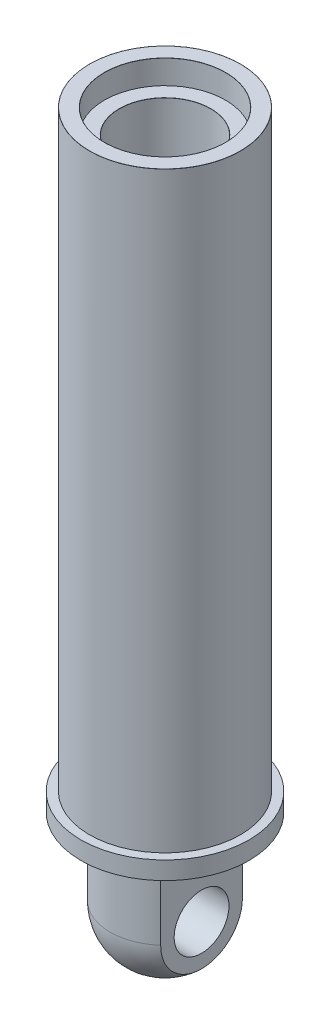
SolidWorks part; units mm, degrees
ref_plane "Front Plane" through (0, 0, 0) normal (0, 0, 1) x (1, 0, 0)
ref_plane "Top Plane" through (0, 0, 0) normal (0, 1, 0) x (1, 0, 0)
ref_plane "Right Plane" through (0, 0, 0) normal (1, 0, 0) x (0, 0, -1)
sketch "Sketch1" plane through (0, 0, 0) normal (0, 0, 1) x (1, 0, 0)
  line L0 (0, 0) -> (0, 300) construction
  line L2 (30.5, 60.44) -> (30.5, 300)
  line L5 (30.5, 300) -> (18.5, 300)
  line L6 (18.5, 300) -> (18.5, 60.44)
  line L7 (18.5, 60.44) -> (0, 60.44)
  line L8 (0, 60.44) -> (0, 0)
  line L9 (22.17, 53.2) -> (34.01, 53.2)
  line L10 (34.01, 53.2) -> (34.01, 60.44)
  line L11 (34.01, 60.44) -> (30.5, 60.44)
  line L16 (22.17, 22.17) -> (22.17, 53.2)
  line L17 (0, 0) -> (44.3568, 0) construction
  arc A2 (0, 0) -> (22.17, 22.17) centre (0, 22.17) ccw
  point P4 (9.25, 60.44)
  dimension "D9" = 22.17
  dimension "D5" = 18.5
  dimension "D3" = 300
  dimension "D1" = 12
  dimension "D4" = 53.2
  dimension "D6" = 7.24
  dimension "D8" = 34.01
revolve "Revolve1" add sketch "Sketch1" angle 360 about L0
cosmetic thread "Cosmetic Thread1" parameters "D1"=146.4852, "D2"=37
sketch "Sketch2" plane through (0, 0, 0) normal (1, 0, 0) x (0, 0, -1)
  circle A0 centre (0, 22.17) radius 11.085
  dimension "D1" = 22.17
  dimension "D2" = 22.17
extrude "Cut-Extrude1" cut sketch "Sketch2" against normal through all both and the other way through all
sketch "Sketch3" plane through (0, 0, 0) normal (0, 0, 1) x (1, 0, 0)
  line L0 (0, 0) -> (0, 49.26) construction
  line L1 (-53.33, 49.26) -> (-53.33, 0)
  line L2 (35.8889, 49.26) -> (53.33, 49.26)
  line L3 (14.78, 28.1481) -> (14.78, 0) construction
  line L4 (14.78, 0) -> (53.33, 0)
  line L5 (53.33, 49.26) -> (53.33, 0)
  line L6 (-35.8889, 49.26) -> (-53.33, 49.26)
  line L7 (-14.78, 0) -> (-53.33, 0)
  line L8 (-14.78, 28.1481) -> (-14.78, 0) construction
  line L9 (14.78, 28.1481) -> (14.78, 49.26)
  line L10 (14.78, 49.26) -> (35.8889, 49.26)
  line L11 (-14.78, 28.1481) -> (-14.78, 49.26)
  line L12 (-14.78, 49.26) -> (-35.8889, 49.26)
  line L13 (-14.78, 28.1481) -> (-14.78, 0)
  line L14 (14.78, 0) -> (14.78, 28.1481)
  arc A1 (-35.8889, 49.26) -> (-14.78, 28.1481) centre (-35.8911, 28.1489) cw construction
  dimension "D1" = 49.26
  dimension "D2" = 38.55
  dimension "D3" = 14.78
extrude "Cut-Extrude2" cut sketch "Sketch3" against normal through all both and the other way through all
fillet "Fillet1" radius 0.1468 3 edges at (22.17, 53.2, 0) (14.78, 49.26, 0) (-14.78, 49.26, 0)
sketch "Sketch8" plane through (0, 300, 0) normal (0, 1, 0) x (1, 0, 0)
  circle A0 centre (0, 0) radius 24.5
  dimension "D1" = 49
extrude "Cut-Extrude3" cut sketch "Sketch8" against normal blind 9.6905
fillet "Fillet4" radius 0.044 3 edges at (30.5, 300, 0) (-24.5, 300, 0) (-18.5, 290.3095, 0)
ref_plane "Plane1" through (0, 160, 0) normal (0, 1, 0) x (1, 0, 0)
equation "\"D5@Sketch1\"=\"Upper_Mount_largest_radius\""
equation "\"D1@Sketch8\"=(2*\"Upper_Mount_largest_radius\")+(\"Upper_mount_wall_thickness\")"
equation "\"Upper_Mount_largest_radius\" =18.5"
equation "\"Upper_mount_wall_thickness\" =12"
equation "\"D1@Sketch1\"=\"Upper_mount_wall_thickness\""
equation "\"D1@Cut-Extrude3\"=(\"Upper_Mount_largest_radius\"*17.6984127)/33.78787879"
equation "\"D1@Fillet4\"=\"Upper_Mount_largest_radius\"/420"
equation "\"Lower_Mount_piston_rod_length\" =149"
equation "\"Lower_Mount_piston_rod_radius\"\t=4.9101"
equation "\"Piston_orifice_dia\"=0.47773"
equation "\"Spring_inner_dia\" =80"
equation "\"Spring_wire_dia\" =8"
equation "\"D2@Cosmetic Thread1\"=\"Upper_Mount_largest_radius\"*2"
equation "\"D1@Fillet1\"=\"Upper_Mount_largest_radius\"/126"
